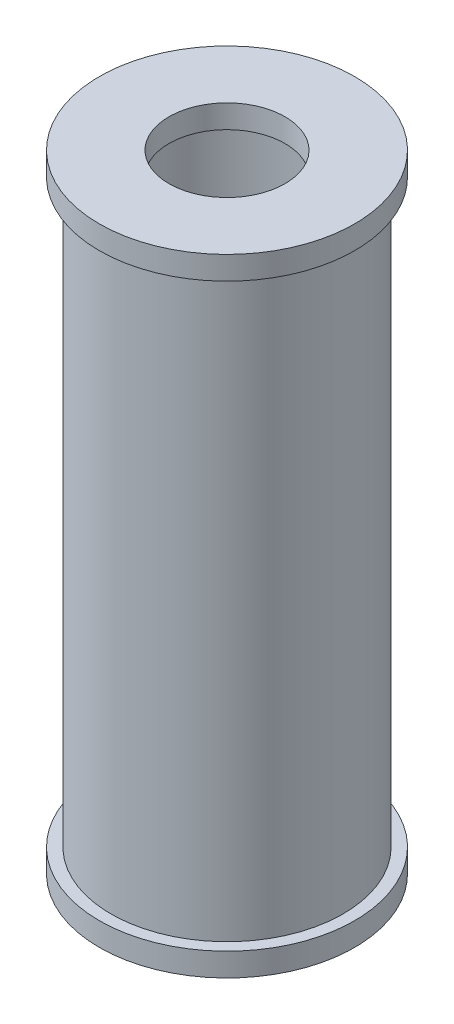
SolidWorks part; units mm, degrees
ref_plane "Alzado" through (0, 0, 0) normal (0, 0, 1) x (1, 0, 0)
ref_plane "Planta" through (0, 0, 0) normal (0, 1, 0) x (1, 0, 0)
ref_plane "Vista lateral" through (0, 0, 0) normal (1, 0, 0) x (0, 0, -1)
sketch "Sketch1" plane through (0, 0, 0) normal (0, 0, 1) x (1, 0, 0)
  line L0 (0, 0) -> (0, 100) construction
  line L1 (18, 100) -> (20, 100)
  line L2 (20, 100) -> (20, 0)
  line L3 (20, 0) -> (18, 0)
  line L4 (18, 100) -> (18, 0)
  dimension "D1" = 100
  dimension "D2" = 20
  dimension "D3" = 18
revolve "Revolve1" add sketch "Sketch1" angle 360 about L0
sketch "Sketch2" plane through (0, 100, 0) normal (0, 1, 0) x (1, 0, 0)
  circle A0 centre (0, 0) radius 22
extrude "Boss-Extrude1" add sketch "Sketch2" along normal blind 4
sketch "Sketch3" plane through (0, 0, 0) normal (0, -1, 0) x (1, 0, 0)
  circle A0 centre (0, 0) radius 22
  dimension "D1" = 44
extrude "Boss-Extrude2" add sketch "Sketch3" along normal blind 4
sketch "Sketch4" plane through (0, 104, 0) normal (0, 1, 0) x (1, 0, 0)
  circle A0 centre (0, 0) radius 10
extrude "Cut-Extrude1" cut sketch "Sketch4" against normal blind 4
